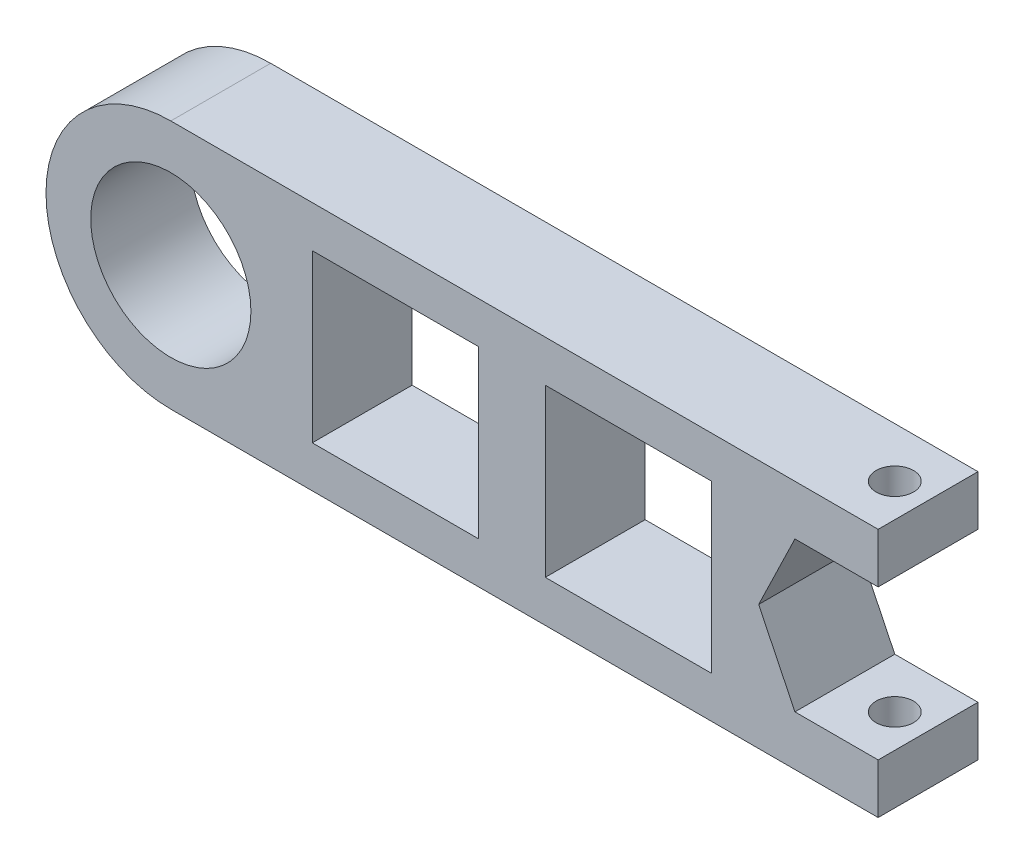
SolidWorks part; units mm, degrees
ref_plane "Front Plane" through (0, 0, 0) normal (0, 0, 1) x (1, 0, 0)
ref_plane "Top Plane" through (0, 0, 0) normal (0, 1, 0) x (1, 0, 0)
ref_plane "Right Plane" through (0, 0, 0) normal (1, 0, 0) x (0, 0, -1)
sketch "Sketch1" plane through (0, 0, 0) normal (0, 0, 1) x (1, 0, 0)
  line L0 (-85, 0) -> (-14.3589, 0) construction
  line L1 (55, 0) -> (-55, 0) construction
  line L2 (-85, 15) -> (0, 15)
  line L3 (-85, -15) -> (0, -15)
  line L4 (0, 15) -> (0, 9)
  line L5 (0, -55) -> (0, 55) construction
  line L6 (0, 9) -> (-10, 9)
  line L7 (-10, 9) -> (-14.3589, 0)
  line L8 (-14.3589, 0) -> (-10, -9)
  line L9 (-10, -9) -> (0, -9)
  line L10 (0, -9) -> (0, -15)
  arc A0 (-85, 15) -> (-85, -15) centre (-85, 0) ccw
  circle A2 centre (-85, 0) radius 9.625
  point P5 (0, 0)
  dimension "D1" = 15
  dimension "D4" = 19.25
  dimension "D5" = 10
  dimension "D2" = 10
  dimension "D3" = 85
  dimension "D6" = 10
  dimension "D7" = 10
  dimension "D8" = 6
  dimension "D9" = 6
  dimension "D10" = 85
extrude "Boss-Extrude1" add sketch "Sketch1" along normal blind 12
sketch "Sketch2" plane through (0, -15, 0) normal (0, -1, 0) x (1, 0, 0)
  line L0 (-85, 12) -> (0, 12) construction
  line L2 (0, -6.6) -> (0, 6.6) construction
  circle A0 centre (-4, 6) radius 2.25
  dimension "D1" = 6
  dimension "D3" = 4.5
  dimension "D2" = 4
extrude "Cut-Extrude1" cut sketch "Sketch2" against normal through all
sketch "Sketch3" plane through (0, 0, 12) normal (0, 0, 1) x (1, 0, 0)
  line L0 (0, -6.6) -> (0, 6.6) construction
  line L1 (-20, 10) -> (-40, 10)
  line L2 (-20, 10) -> (-20, -10)
  line L3 (-20, -10) -> (-40, -10)
  line L4 (-40, 10) -> (-40, -10)
  line L5 (-48, 10) -> (-68, 10)
  line L6 (-48, 10) -> (-48, -10)
  line L7 (-48, -10) -> (-68, -10)
  line L8 (-68, 10) -> (-68, -10)
  line L9 (0, 15) -> (-85, 15) construction
  dimension "D1" = 20
  dimension "D2" = 20
  dimension "D3" = 20
  dimension "D4" = 20
  dimension "D5" = 20
  dimension "D6" = 8
  dimension "D7" = 5
  dimension "D8" = 5
extrude "Cut-Extrude2" cut sketch "Sketch3" against normal through all
